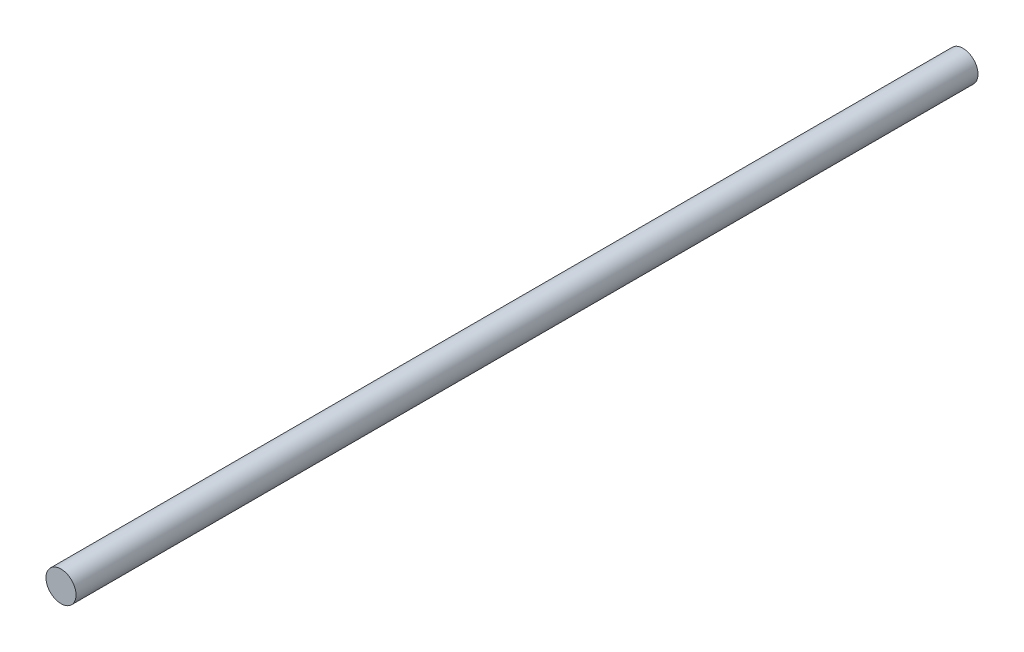
SolidWorks part; units mm, degrees
material "AISI 304"
ref_plane "前视基准面" through (0, 0, 0) normal (0, 0, 1) x (1, 0, 0)
ref_plane "上视基准面" through (0, 0, 0) normal (0, 1, 0) x (1, 0, 0)
ref_plane "右视基准面" through (0, 0, 0) normal (1, 0, 0) x (0, 0, -1)
sketch "草图1" plane through (0, 0, 0) normal (0, 0, 1) x (1, 0, 0)
  circle A0 centre (0, 0) radius 0.5
  dimension "D1" = 1
extrude "凸台-拉伸1" add sketch "草图1" along normal blind 30
